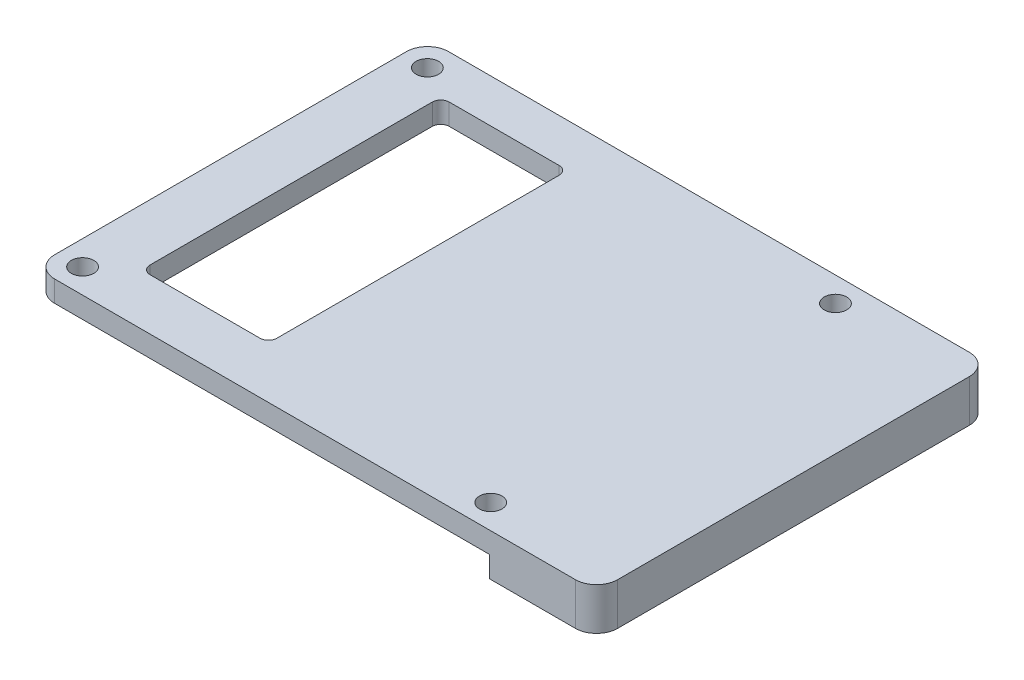
SolidWorks part; units mm, degrees
material "7075-T6 (SN)"
ref_plane "前视基准面" through (0, 0, 0) normal (0, 0, 1) x (1, 0, 0)
ref_plane "上视基准面" through (0, 0, 0) normal (0, 1, 0) x (1, 0, 0)
ref_plane "右视基准面" through (0, 0, 0) normal (1, 0, 0) x (0, 0, -1)
other "Configuration Table"
sketch "草图1" plane through (0, 0, 0) normal (0, 1, 0) x (1, 0, 0)
  line L0 (-70.9525, 18.3001) -> (-70.9986, 18.1669) construction
  line L5 (-80.009, 21.4027) -> (-0.009, 21.4027) construction
  line L6 (-0.009, 21.39) -> (-0.009, -28.5917)
  line L7 (-53.9406, -24.2884) -> (-53.9406, -23.4455) construction
  line L12 (-80.009, 21.4027) -> (-80.009, -28.6044)
  line L13 (-77.0217, -31.5917) -> (12.7873, -31.5917)
  line L14 (15.7746, -28.6044) -> (15.7746, 21.4027)
  line L15 (12.7873, 24.39) -> (-77.0217, 24.39)
  line L16 (-80.009, 21.4027) -> (-80.009, -28.6044)
  line L17 (-77.0217, -31.5917) -> (-3.009, -31.5917)
  line L19 (-3.009, 24.39) -> (-77.0217, 24.39)
  line L20 (-57.0741, 18.2303) -> (-57.0142, 16.884) construction
  line L21 (-57.0142, 16.884) -> (-53.9406, 15.8369) construction
  line L24 (-71.9124, -31.5917) -> (-71.9124, -38.4632) construction
  line L26 (-55.8106, -26.0508) -> (-55.3191, -21.9005) construction
  line L27 (-55.3191, -21.9005) -> (-52.2337, -21.9005) construction
  line L28 (-57.0741, 18.2303) -> (-53.9406, 18.2303) construction
  line L30 (-53.9406, 15.8369) -> (-53.9406, 18.2303) construction
  line L31 (-71.9686, 17.09) -> (-71.9659, 15.0188) construction
  line L32 (-54.4169, -24.2884) -> (-53.9406, -24.2884) construction
  line L33 (-70.9986, 18.1669) -> (-70.8339, 18.1567) construction
  line L34 (-70.8339, 18.1567) -> (-70.8158, 18.2696) construction
  line L35 (-70.8158, 18.2696) -> (-70.9525, 18.3001) construction
  line L36 (-70.8221, 18.2303) -> (-69.2002, 18.2303) construction
  line L38 (-70.7701, 18.2303) -> (-55.1406, 18.2303)
  line L39 (-71.9701, 17.0303) -> (-71.9701, -23.0884)
  line L40 (-70.7701, -24.2884) -> (-55.1406, -24.2884)
  line L41 (-53.9406, 17.0303) -> (-53.9406, -23.0884)
  arc A0 (-70.7701, 18.2303) -> (-71.9701, 17.0303) centre (-70.7701, 17.0303) ccw
  arc A1 (-53.9406, 17.0303) -> (-55.1406, 18.2303) centre (-55.1406, 17.0303) ccw
  arc A2 (-53.9406, -23.0884) -> (-55.1406, -24.2884) centre (-55.1406, -23.0884) cw
  arc A3 (-70.7701, -24.2884) -> (-71.9701, -23.0884) centre (-70.7701, -23.0884) cw
  circle A4 centre (-76.5285, 20.8867) radius 1.6
  circle A5 centre (-18.5286, 20.8866) radius 1.6
  circle A6 centre (-18.5283, -28.1137) radius 1.6
  circle A7 centre (-76.5283, -28.1135) radius 1.6
  arc A8 (-80.009, -28.6044) -> (-77.0217, -31.5917) centre (-77.0217, -28.6044) ccw
  arc A9 (12.7873, -31.5917) -> (15.7746, -28.6044) centre (12.7873, -28.6044) ccw
  arc A10 (15.7746, 21.4027) -> (12.7873, 24.39) centre (12.7873, 21.4027) ccw
  arc A11 (-77.0217, 24.39) -> (-80.009, 21.4027) centre (-77.0217, 21.4027) ccw
  arc A12 (-80.009, -28.6044) -> (-77.0217, -31.5917) centre (-77.0217, -28.6044) ccw
  arc A15 (-77.0217, 24.39) -> (-80.009, 21.4027) centre (-77.0217, 21.4027) ccw
  arc A19 (-0.009, 21.39) -> (-3.009, 24.39) centre (-3.009, 21.39) ccw
  arc A20 (-0.009, -28.5917) -> (-3.009, -31.5917) centre (-3.009, -28.5917) cw
  dimension "D2" = 3.2
  dimension "D3" = 3.2
  dimension "D4" = 3.2
  dimension "D5" = 3.2
  dimension "D6" = 3
  dimension "D7" = 1.2
  dimension "D8" = 1.2
  dimension "D9" = 1.2
  dimension "D10" = 1.2
  dimension "D11" = 3
  dimension "D1" = 0
extrude "凸台-拉伸1" add sketch "草图1" along normal blind 3
sketch "草图3" plane through (0, 0, 0) normal (0, -1, 0) x (1, 0, 0)
  line L0 (-77.0217, 31.5917) -> (-3.009, 31.5917) construction
  line L1 (-15.2271, 31.5917) -> (-3.009, 31.5917)
  line L2 (-15.2271, 31.5917) -> (-15.2271, -24.39)
  line L3 (-15.2271, -24.39) -> (-3.009, -24.39)
  line L11 (-0.009, 28.5917) -> (-0.009, -21.39)
  arc A0 (-0.009, -21.39) -> (-3.009, -24.39) centre (-3.009, -21.39) cw
  arc A1 (-3.009, 31.5917) -> (-0.009, 28.5917) centre (-3.009, 28.5917) cw
  dimension "D1" = 3
  dimension "D2" = 3
extrude "凸台-拉伸3" add sketch "草图3" along normal blind 3
sketch "草图4" plane through (0, 0, 0) normal (0, -1, 0) x (1, 0, 0)
  line L0 (-80.009, 24.3217) -> (-76.6695, 24.3217)
  line L1 (-80.009, -21.4027) -> (-80.009, 28.6044) construction
  line L2 (-15.2271, 31.5917) -> (-15.2271, -24.39) construction
  line L3 (-15.2271, 24.3217) -> (-15.2271, 31.5917)
  line L4 (-15.2271, 31.5917) -> (-21.7271, 31.5917)
  line L5 (-77.0217, 31.5917) -> (-15.2271, 31.5917) construction
  line L6 (-21.7271, 31.5917) -> (-21.7271, 27.3217)
  line L7 (-21.7271, -21.1423) -> (-21.7271, -24.39)
  line L8 (-73.6695, 27.3217) -> (-73.6695, 31.5917)
  line L9 (-18.7271, 24.3217) -> (-15.2271, 24.3217)
  line L10 (-80.009, 24.3217) -> (-80.009, 28.5917)
  line L11 (-77.009, 31.5917) -> (-73.6695, 31.5917)
  line L16 (-80.009, -18.1423) -> (-76.6695, -18.1423)
  line L17 (-73.6695, -21.1423) -> (-73.6695, -24.3882)
  line L18 (-73.6695, -24.3882) -> (-77.009, -24.3882)
  line L19 (-80.009, -21.3882) -> (-80.009, -18.1423)
  line L20 (-18.7271, -18.1423) -> (-15.2271, -18.1423) construction
  line L21 (-18.7271, -18.1423) -> (-15.2271, -18.1423)
  line L22 (-15.2271, -18.1423) -> (-15.2271, -24.39)
  line L23 (-15.2271, -24.39) -> (-21.7271, -24.39)
  line L24 (-15.2271, -24.39) -> (-77.0217, -24.39) construction
  line L25 (-73.6695, -19.7285) -> (-73.6695, -28.5591) construction
  line L34 (-76.6695, -18.1423) -> (-92.8145, -18.1423) construction
  circle A0 centre (-76.5283, 28.1135) radius 1.6
  circle A1 centre (-18.5283, 28.1137) radius 1.6
  circle A2 centre (-18.5286, -20.8866) radius 1.6
  circle A3 centre (-76.5285, -20.8867) radius 1.6
  arc A4 (-80.009, 28.5917) -> (-77.009, 31.5917) centre (-77.009, 28.5917) cw
  arc A6 (-77.009, -24.3882) -> (-80.009, -21.3882) centre (-77.009, -21.3882) cw
  arc A10 (-18.7271, 24.3217) -> (-21.7271, 27.3217) centre (-18.7271, 27.3217) cw
  arc A11 (-18.7271, -18.1423) -> (-21.7271, -21.1423) centre (-18.7271, -21.1423) ccw
  arc A12 (-73.6695, -21.1423) -> (-76.6695, -18.1423) centre (-76.6695, -21.1423) ccw
  arc A13 (-73.6695, 27.3217) -> (-76.6695, 24.3217) centre (-76.6695, 27.3217) cw
  point P45 (-73.6695, -18.1423)
  point P57 (-21.7271, 24.3217)
  dimension "D1" = 3
  dimension "D2" = 3
  dimension "D3" = 3
  dimension "D4" = 3
  dimension "D5" = 3
  dimension "D6" = 3
  dimension "D7" = 6.5
  dimension "D8" = 6.5
